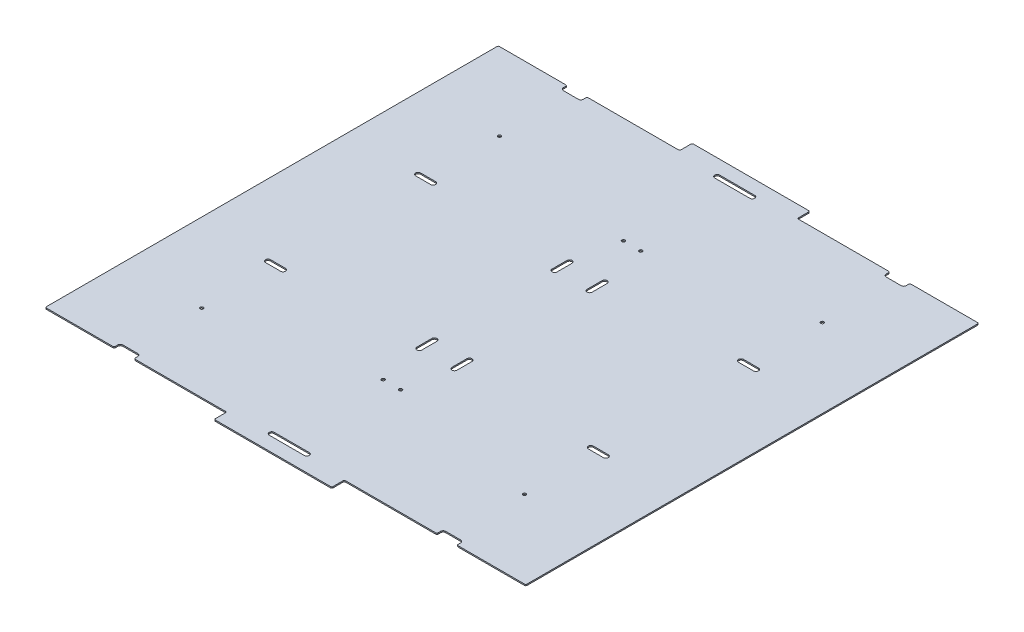
SolidWorks part; units mm, degrees
material "PC High Viscosity"
ref_plane "Front Plane" through (0, 0, 0) normal (0, 0, 1) x (1, 0, 0)
ref_plane "Top Plane" through (0, 0, 0) normal (0, 1, 0) x (1, 0, 0)
ref_plane "Right Plane" through (0, 0, 0) normal (1, 0, 0) x (0, 0, -1)
sketch "Sketch1" plane through (0, 0, 0) normal (0, 1, 0) x (1, 0, 0)
  line L1 (-609.6, -609.6) -> (609.6, -609.6)
  line L2 (-609.6, -609.6) -> (-609.6, 609.6)
  line L3 (-609.6, 609.6) -> (609.6, 609.6)
  line L4 (609.6, -609.6) -> (609.6, 609.6)
  line L5 (-609.6, -609.6) -> (609.6, 609.6) construction
  line L6 (-609.6, 609.6) -> (609.6, -609.6) construction
  point P0 (0, 0)
  dimension "D1" = 1219.2
  dimension "D2" = 1219.2
extrude "Boss-Extrude1" add sketch "Sketch1" along normal blind 3.175
hole_wizard "5/16 (0.3125) Diameter Hole1" positions "Sketch3" profile "Sketch4" hole size "5/16" standard "ANSI Inch" end condition through all
sketch "Sketch3" plane through (0, 3.175, 0) normal (0, 1, 0) x (1, 0, 0)
  line L0 (-609.6, 609.6) -> (-609.6, -609.6) construction
  line L1 (0, -609.6) -> (0, 609.6) construction
  line L4 (609.6, 0) -> (-609.6, 0) construction
  line L5 (609.6, -609.6) -> (609.6, 609.6) construction
  line L7 (609.6, 609.6) -> (-609.6, 609.6) construction
  line L8 (-609.6, -609.6) -> (609.6, -609.6) construction
  point P0 (-409.575, 377.825)
  point P2 (-22.225, 304.8)
  point P23 (22.225, 304.8)
  point P24 (409.575, 377.825)
  point P25 (-22.225, -304.8)
  point P26 (-409.575, -377.825)
  point P27 (409.575, -377.825)
  point P28 (22.225, -304.8)
  dimension "D1" = 377.825
  dimension "D2" = 22.225
  dimension "D3" = 409.575
  dimension "D4" = 304.8
sketch "Sketch4" plane through (-409.575, 3.175, -377.825) normal (1, 0, 0) x (0, 0, 1)
  line L0 (0, 0) -> (0, 3.175)
  line L1 (0, 3.175) -> (3.9687, 3.175)
  line L2 (3.9687, 3.175) -> (3.9687, 0)
  line L5 (3.9687, 0) -> (0, 0)
  line L11 (0, -6.35) -> (0, 107.95) construction
  dimension "Thru Hole Dia." = 7.9375
  dimension "Thru Hole Depth" = 3.175
sketch "Sketch5" plane through (0, 3.175, 0) normal (0, 1, 0) x (1, 0, 0)
  line L0 (-609.6, 574.675) -> (-149.225, 574.675)
  line L1 (-609.6, 609.6) -> (-152.4, 609.6) construction
  line L2 (-609.6, 609.6) -> (-609.6, 577.85) construction
  line L3 (-609.6, 577.85) -> (-152.4, 577.85) construction
  line L4 (-152.4, 609.6) -> (-152.4, 577.85) construction
  line L5 (-149.225, 609.6) -> (-149.225, 574.675)
  line L6 (-609.6, 574.675) -> (-609.6, 609.6)
  line L7 (-149.225, 609.6) -> (-609.6, 609.6)
  line L8 (0, 609.6) -> (0, -609.6) construction
  line L9 (609.6, 609.6) -> (-609.6, 609.6) construction
  line L10 (-609.6, -609.6) -> (609.6, -609.6) construction
  line L11 (609.6, 0) -> (-609.6, 0) construction
  line L12 (609.6, -609.6) -> (609.6, 609.6) construction
  line L13 (-609.6, 609.6) -> (-609.6, -609.6) construction
  line L14 (149.225, 609.6) -> (149.225, 574.675)
  line L15 (609.6, 574.675) -> (149.225, 574.675)
  line L16 (609.6, 574.675) -> (609.6, 609.6)
  line L17 (149.225, 609.6) -> (609.6, 609.6)
  line L18 (149.225, -609.6) -> (609.6, -609.6)
  line L19 (609.6, -574.675) -> (609.6, -609.6)
  line L20 (609.6, -574.675) -> (149.225, -574.675)
  line L21 (149.225, -609.6) -> (149.225, -574.675)
  line L22 (-609.6, -574.675) -> (-609.6, -609.6)
  line L23 (-609.6, -574.675) -> (-149.225, -574.675)
  line L24 (-149.225, -609.6) -> (-149.225, -574.675)
  line L25 (-149.225, -609.6) -> (-609.6, -609.6)
  dimension "D1" = 31.75
  dimension "D2" = 457.2
  dimension "D3" = 3.175
extrude "Cut-Extrude1" cut sketch "Sketch5" against normal through all
sketch "Sketch6" plane through (0, 3.175, 0) normal (0, 1, 0) x (1, 0, 0)
  line L0 (149.225, 609.6) -> (-149.225, 609.6) construction
  line L1 (-44.45, 609.6) -> (0, 609.6)
  line L2 (-44.45, 609.6) -> (-44.45, -609.6)
  line L3 (-44.45, -609.6) -> (0, -609.6)
  line L4 (0, 609.6) -> (0, -609.6)
  line L5 (-149.225, -609.6) -> (149.225, -609.6) construction
  line L6 (0, -609.6) -> (0, 609.6) construction
  line L7 (-609.6, 574.675) -> (-609.6, -574.675) construction
  line L8 (-44.45, 609.6) -> (-609.6, 609.6)
  line L9 (-44.45, 609.6) -> (-44.45, 565.15)
  line L10 (-44.45, 565.15) -> (-609.6, 565.15)
  line L11 (-609.6, 609.6) -> (-609.6, 565.15)
  line L12 (609.6, 0) -> (-609.6, 0) construction
  line L17 (609.6, -574.675) -> (609.6, 574.675) construction
  line L18 (609.6, 190.5) -> (609.6, 152.4)
  line L19 (-428.625, 565.15) -> (-390.525, 565.15)
  line L20 (-428.625, 565.15) -> (-428.625, 190.5)
  line L21 (-428.625, 190.5) -> (-390.525, 190.5)
  line L22 (-390.525, 565.15) -> (-390.525, 190.5)
  line L23 (-44.45, 190.5) -> (-609.6, 190.5)
  line L24 (-44.45, 190.5) -> (-44.45, 152.4)
  line L25 (-44.45, 152.4) -> (-609.6, 152.4)
  line L26 (-609.6, 190.5) -> (-609.6, 152.4)
  line L27 (44.45, 152.4) -> (609.6, 152.4)
  line L28 (44.45, 190.5) -> (44.45, 152.4)
  line L29 (44.45, 190.5) -> (609.6, 190.5)
  line L30 (390.525, 565.15) -> (390.525, 190.5)
  line L31 (428.625, 190.5) -> (390.525, 190.5)
  line L32 (428.625, 565.15) -> (428.625, 190.5)
  line L33 (428.625, 565.15) -> (390.525, 565.15)
  line L34 (609.6, 609.6) -> (609.6, 565.15)
  line L35 (44.45, 565.15) -> (609.6, 565.15)
  line L36 (44.45, 609.6) -> (44.45, 565.15)
  line L37 (44.45, 609.6) -> (609.6, 609.6)
  line L38 (0, 609.6) -> (0, -609.6)
  line L39 (44.45, -609.6) -> (0, -609.6)
  line L40 (44.45, 609.6) -> (44.45, -609.6)
  line L41 (44.45, 609.6) -> (0, 609.6)
  line L42 (44.45, -609.6) -> (0, -609.6)
  line L43 (44.45, 609.6) -> (0, 609.6)
  line L44 (44.45, -609.6) -> (609.6, -609.6)
  line L45 (44.45, -609.6) -> (44.45, -565.15)
  line L46 (44.45, -565.15) -> (609.6, -565.15)
  line L47 (609.6, -609.6) -> (609.6, -565.15)
  line L48 (428.625, -565.15) -> (390.525, -565.15)
  line L49 (428.625, -565.15) -> (428.625, -190.5)
  line L50 (428.625, -190.5) -> (390.525, -190.5)
  line L51 (390.525, -565.15) -> (390.525, -190.5)
  line L52 (44.45, -190.5) -> (609.6, -190.5)
  line L53 (44.45, -190.5) -> (44.45, -152.4)
  line L54 (44.45, -152.4) -> (609.6, -152.4)
  line L55 (-609.6, -190.5) -> (-609.6, -152.4)
  line L56 (-44.45, -152.4) -> (-609.6, -152.4)
  line L57 (-44.45, -190.5) -> (-44.45, -152.4)
  line L58 (-44.45, -190.5) -> (-609.6, -190.5)
  line L59 (-390.525, -565.15) -> (-390.525, -190.5)
  line L60 (-428.625, -190.5) -> (-390.525, -190.5)
  line L61 (-428.625, -565.15) -> (-428.625, -190.5)
  line L62 (-428.625, -565.15) -> (-390.525, -565.15)
  line L63 (609.6, -190.5) -> (609.6, -152.4)
  line L64 (-609.6, -609.6) -> (-609.6, -565.15)
  line L65 (-44.45, -565.15) -> (-609.6, -565.15)
  line L66 (-44.45, -609.6) -> (-44.45, -565.15)
  line L67 (-44.45, -609.6) -> (-609.6, -609.6)
  line L68 (-44.45, 609.6) -> (0, 609.6)
  line L69 (-44.45, -609.6) -> (0, -609.6)
  line L70 (-409.575, 190.5) -> (-409.575, 565.15) construction
  circle A0 centre (-409.575, 377.825) radius 3.9688 construction
  circle A1 centre (-409.575, 377.825) radius 3.9688
  dimension "D1" = 38.1
  dimension "D2" = 44.45
  dimension "D3" = 304.8
sketch "Sketch7" plane through (0, 3.175, 0) normal (0, 1, 0) x (1, 0, 0)
  line L0 (-428.625, 565.15) -> (-390.525, 565.15) construction
  line L1 (-428.625, 571.5) -> (-390.525, 571.5)
  line L2 (-428.625, 558.8) -> (-390.525, 558.8)
  line L3 (-428.625, 190.5) -> (-390.525, 190.5) construction
  line L4 (-428.625, 196.85) -> (-390.525, 196.85)
  line L5 (-428.625, 184.15) -> (-390.525, 184.15)
  line L6 (-44.45, 565.15) -> (44.45, 565.15) construction
  line L17 (-44.45, 190.5) -> (-44.45, 152.4) construction
  line L20 (-38.1, 190.5) -> (-38.1, 152.4)
  line L23 (-50.8, 190.5) -> (-50.8, 152.4)
  line L26 (609.6, 0) -> (-609.6, 0) construction
  line L27 (-609.6, 574.675) -> (-609.6, -574.675) construction
  line L28 (-428.625, -565.15) -> (-390.525, -565.15) construction
  line L29 (-428.625, -571.5) -> (-390.525, -571.5)
  line L30 (-428.625, -558.8) -> (-390.525, -558.8)
  line L31 (-428.625, -190.5) -> (-390.525, -190.5) construction
  line L32 (-428.625, -196.85) -> (-390.525, -196.85)
  line L33 (-428.625, -184.15) -> (-390.525, -184.15)
  line L34 (-149.225, -609.6) -> (-149.225, -574.675) construction
  line L37 (-44.45, -190.5) -> (-44.45, -152.4) construction
  line L38 (-38.1, -190.5) -> (-38.1, -152.4)
  line L39 (-50.8, -190.5) -> (-50.8, -152.4)
  line L40 (0, -609.6) -> (0, 0) construction
  line L41 (-149.225, -609.6) -> (149.225, -609.6) construction
  line L43 (428.625, 565.15) -> (390.525, 565.15) construction
  line L44 (428.625, 571.5) -> (390.525, 571.5)
  line L45 (428.625, 558.8) -> (390.525, 558.8)
  line L46 (428.625, 190.5) -> (390.525, 190.5) construction
  line L47 (428.625, 196.85) -> (390.525, 196.85)
  line L48 (428.625, 184.15) -> (390.525, 184.15)
  line L49 (-44.45, 571.5) -> (44.45, 571.5)
  line L52 (44.45, 190.5) -> (44.45, 152.4) construction
  line L53 (38.1, 190.5) -> (38.1, 152.4)
  line L54 (50.8, 190.5) -> (50.8, 152.4)
  line L55 (428.625, -565.15) -> (390.525, -565.15) construction
  line L56 (428.625, -571.5) -> (390.525, -571.5)
  line L57 (428.625, -558.8) -> (390.525, -558.8)
  line L58 (428.625, -190.5) -> (390.525, -190.5) construction
  line L59 (428.625, -196.85) -> (390.525, -196.85)
  line L60 (428.625, -184.15) -> (390.525, -184.15)
  line L64 (44.45, -190.5) -> (44.45, -152.4) construction
  line L65 (38.1, -190.5) -> (38.1, -152.4)
  line L66 (50.8, -190.5) -> (50.8, -152.4)
  line L67 (-149.225, 574.675) -> (-149.225, 609.6) construction
  line L68 (-44.45, 558.8) -> (44.45, 558.8)
  line L69 (-44.45, -565.15) -> (44.45, -565.15) construction
  line L70 (-44.45, -558.8) -> (44.45, -558.8)
  line L71 (-44.45, -571.5) -> (44.45, -571.5)
  arc A0 (-428.625, 571.5) -> (-428.625, 558.8) centre (-428.625, 565.15) ccw
  arc A1 (-390.525, 558.8) -> (-390.525, 571.5) centre (-390.525, 565.15) ccw
  arc A2 (-428.625, 196.85) -> (-428.625, 184.15) centre (-428.625, 190.5) ccw
  arc A3 (-390.525, 184.15) -> (-390.525, 196.85) centre (-390.525, 190.5) ccw
  arc A18 (-38.1, 190.5) -> (-50.8, 190.5) centre (-44.45, 190.5) ccw
  arc A19 (-50.8, 152.4) -> (-38.1, 152.4) centre (-44.45, 152.4) ccw
  arc A20 (-428.625, -571.5) -> (-428.625, -558.8) centre (-428.625, -565.15) cw
  arc A21 (-390.525, -558.8) -> (-390.525, -571.5) centre (-390.525, -565.15) cw
  arc A22 (-428.625, -196.85) -> (-428.625, -184.15) centre (-428.625, -190.5) cw
  arc A23 (-390.525, -184.15) -> (-390.525, -196.85) centre (-390.525, -190.5) cw
  arc A26 (-38.1, -190.5) -> (-50.8, -190.5) centre (-44.45, -190.5) cw
  arc A27 (-50.8, -152.4) -> (-38.1, -152.4) centre (-44.45, -152.4) cw
  arc A28 (428.625, 571.5) -> (428.625, 558.8) centre (428.625, 565.15) cw
  arc A29 (390.525, 558.8) -> (390.525, 571.5) centre (390.525, 565.15) cw
  arc A30 (428.625, 196.85) -> (428.625, 184.15) centre (428.625, 190.5) cw
  arc A31 (390.525, 184.15) -> (390.525, 196.85) centre (390.525, 190.5) cw
  arc A34 (38.1, 190.5) -> (50.8, 190.5) centre (44.45, 190.5) cw
  arc A35 (50.8, 152.4) -> (38.1, 152.4) centre (44.45, 152.4) cw
  arc A36 (428.625, -571.5) -> (428.625, -558.8) centre (428.625, -565.15) ccw
  arc A37 (390.525, -558.8) -> (390.525, -571.5) centre (390.525, -565.15) ccw
  arc A38 (428.625, -196.85) -> (428.625, -184.15) centre (428.625, -190.5) ccw
  arc A39 (390.525, -184.15) -> (390.525, -196.85) centre (390.525, -190.5) ccw
  arc A42 (38.1, -190.5) -> (50.8, -190.5) centre (44.45, -190.5) ccw
  arc A43 (50.8, -152.4) -> (38.1, -152.4) centre (44.45, -152.4) ccw
  arc A44 (-44.45, 571.5) -> (-44.45, 558.8) centre (-44.45, 565.15) ccw
  arc A45 (44.45, 558.8) -> (44.45, 571.5) centre (44.45, 565.15) ccw
  arc A46 (-44.45, -558.8) -> (-44.45, -571.5) centre (-44.45, -565.15) ccw
  arc A47 (44.45, -571.5) -> (44.45, -558.8) centre (44.45, -565.15) ccw
  point P4 (-409.575, 565.15)
  point P9 (-409.575, 190.5)
  point P19 (0, 565.15)
  point P21 (0, -565.15)
  point P27 (-44.45, 171.45)
  point P41 (-409.575, -565.15)
  point P50 (-409.575, -190.5)
  point P68 (-44.45, -171.45)
  point P89 (409.575, 565.15)
  point P96 (409.575, 190.5)
  point P110 (44.45, 171.45)
  point P117 (409.575, -565.15)
  point P124 (409.575, -190.5)
  point P138 (44.45, -171.45)
  dimension "D1" = 6.35
  dimension "D4" = 104.775
  dimension "D6" = 6.35
  dimension "D8" = 6.35
  dimension "D2" = 44.45
  dimension "D3" = 88.9
  dimension "D5" = 88.9
  dimension "D7" = 104.775
extrude "Cut-Extrude2" cut sketch "Sketch7" against normal through all
sketch "Sketch8" plane through (0, 3.175, 0) normal (0, 1, 0) x (1, 0, 0)
  line L1 (-434.975, -565.15) -> (-384.175, -565.15)
  line L2 (-434.975, -565.15) -> (-434.975, -574.675)
  line L3 (-434.975, -574.675) -> (-384.175, -574.675)
  line L4 (-384.175, -565.15) -> (-384.175, -574.675)
  line L5 (-149.225, -574.675) -> (-609.6, -574.675) construction
  line L6 (609.6, 0) -> (-609.6, 0) construction
  line L7 (609.6, -574.675) -> (609.6, 574.675) construction
  line L8 (-609.6, 574.675) -> (-609.6, -574.675) construction
  line L9 (0, -609.6) -> (0, 609.6) construction
  line L10 (-149.225, -609.6) -> (149.225, -609.6) construction
  line L11 (149.225, 609.6) -> (-149.225, 609.6) construction
  line L12 (384.175, -565.15) -> (384.175, -574.675)
  line L13 (434.975, -574.675) -> (384.175, -574.675)
  line L14 (434.975, -565.15) -> (434.975, -574.675)
  line L15 (434.975, -565.15) -> (384.175, -565.15)
  line L16 (434.975, 565.15) -> (384.175, 565.15)
  line L17 (434.975, 565.15) -> (434.975, 574.675)
  line L18 (434.975, 574.675) -> (384.175, 574.675)
  line L19 (384.175, 565.15) -> (384.175, 574.675)
  line L20 (-384.175, 565.15) -> (-384.175, 574.675)
  line L21 (-434.975, 574.675) -> (-384.175, 574.675)
  line L22 (-434.975, 565.15) -> (-434.975, 574.675)
  line L23 (-434.975, 565.15) -> (-384.175, 565.15)
  arc A0 (-428.625, -558.8) -> (-428.625, -571.5) centre (-428.625, -565.15) ccw construction
  arc A1 (-390.525, -571.5) -> (-390.525, -558.8) centre (-390.525, -565.15) ccw construction
extrude "Cut-Extrude3" cut sketch "Sketch8" against normal through all
sketch "Sketch9" plane through (0, 0, 0) normal (0, -1, 0) x (1, 0, 0)
  line L1 (-149.225, 609.6) -> (149.225, 609.6)
  line L2 (-149.225, 609.6) -> (-149.225, 606.425)
  line L3 (-149.225, 606.425) -> (149.225, 606.425)
  line L4 (149.225, 609.6) -> (149.225, 606.425)
  line L5 (149.225, 574.675) -> (149.225, 609.6) construction
  line L6 (609.6, 0) -> (-609.6, 0) construction
  line L7 (609.6, 574.675) -> (609.6, -574.675) construction
  line L8 (-609.6, -574.675) -> (-609.6, 574.675) construction
  line L9 (149.225, -609.6) -> (149.225, -606.425)
  line L10 (-149.225, -606.425) -> (149.225, -606.425)
  line L11 (-149.225, -609.6) -> (-149.225, -606.425)
  line L12 (-149.225, -609.6) -> (149.225, -609.6)
  dimension "D1" = 1212.85
extrude "Cut-Extrude4" cut sketch "Sketch9" against normal through all
fillet "Fillet1" radius 3.175 20 edges at (-609.6, 1.5875, 574.675) (149.225, 1.5875, 574.675) (609.6, 1.5875, 574.675) (609.6, 1.5875, -574.675) (149.225, 1.5875, -574.675) (-149.225, 1.5875, -574.675) (-609.6, 1.5875, -574.675) (-149.225, 1.5875, 574.675) (-434.975, 1.5875, -574.675) (-434.975, 1.5875, 574.675) (384.175, 1.5875, 574.675) (434.975, 1.5875, 574.675) (434.975, 1.5875, -574.675) (384.175, 1.5875, -574.675) (-384.175, 1.5875, -574.675) (-384.175, 1.5875, 574.675) (149.225, 1.5875, -606.425) (149.225, 1.5875, 606.425) (-149.225, 1.5875, 606.425) (-149.225, 1.5875, -606.425)
